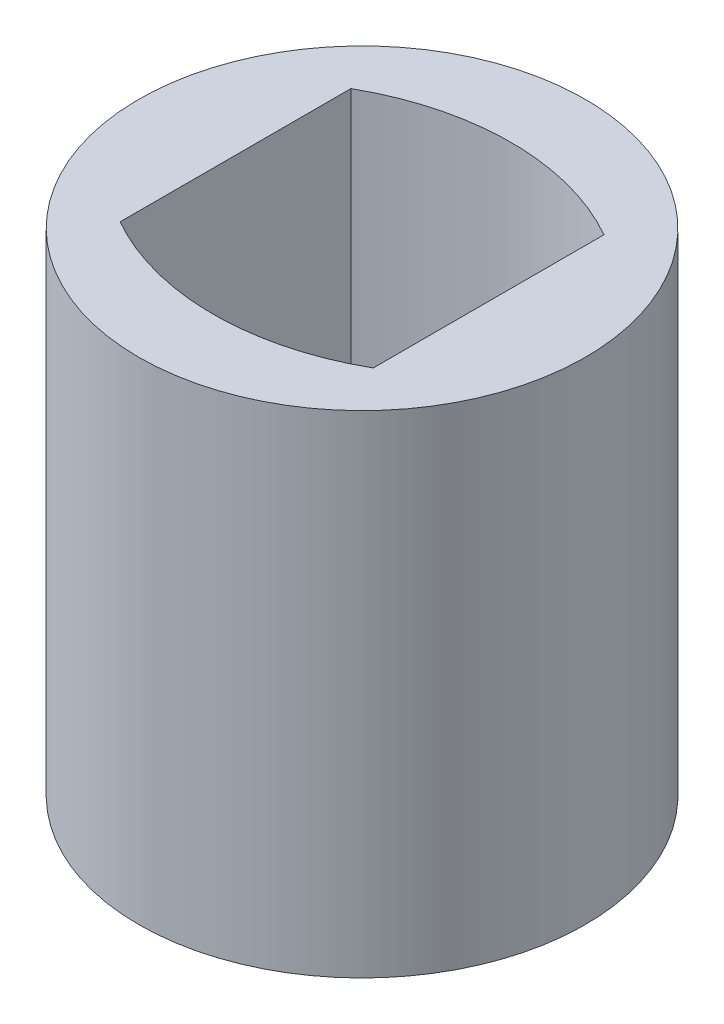
SolidWorks part; units mm, degrees
ref_plane "Front Plane" through (0, 0, 0) normal (0, 0, 1) x (1, 0, 0)
ref_plane "Top Plane" through (0, 0, 0) normal (0, 1, 0) x (1, 0, 0)
ref_plane "Right Plane" through (0, 0, 0) normal (1, 0, 0) x (0, 0, -1)
sketch "Sketch2" plane through (0, 0, 0) normal (0, 1, 0) x (1, 0, 0)
  circle A0 centre (0, 0) radius 3.81
  dimension "D1" = 7.62
extrude "Boss-Extrude1" add sketch "Sketch2" along normal mid plane 2.54
sketch "Sketch3" plane through (0, -1.27, 0) normal (0, -1, 0) x (1, 0, 0)
  line L0 (-0.889, 1.0922) -> (-0.889, -1.0922)
  line L1 (0.889, 1.0922) -> (0.889, -1.0922)
  line L2 (-1.8541, 0) -> (3.3125, 0) construction
  line L3 (0, 1.6302) -> (0, -1.2135) construction
  arc A0 (-0.889, 1.0922) -> (0.889, 1.0922) centre (0, -0.0519) cw
  arc A1 (-0.889, -1.0922) -> (0.889, -1.0922) centre (0, 0.0519) ccw
  point P7 (0.889, 0)
  point P8 (-0.889, 0)
  point P13 (0, 1.397)
  point P14 (0, -1.397)
  dimension "D1" = 2.1844
  dimension "D2" = 1.778
  dimension "D3" = 2.794
extrude "Boss-Extrude2" add sketch "Sketch3" along normal blind 1.27
sketch "Sketch4" plane through (0, 1.27, 0) normal (0, 1, 0) x (1, 0, 0)
  line L0 (-2.159, 1.9685) -> (-2.159, -1.9685)
  line L1 (2.159, 1.9685) -> (2.159, -1.9685)
  line L2 (-1.7553, 0) -> (1.9988, 0) construction
  line L3 (0, 1.4661) -> (0, -1.5676) construction
  arc A0 (-2.159, -1.9685) -> (2.159, -1.9685) centre (0, 1.8239) ccw
  arc A1 (-2.159, 1.9685) -> (2.159, 1.9685) centre (0, -1.8239) cw
  point P11 (-8.4414, 2.6938)
  point P12 (-2.159, 1.2936)
  point P13 (2.159, 1.4661)
  point P14 (2.159, 0)
  point P15 (-2.159, 0)
  point P16 (0, 2.54)
  point P17 (0, -2.54)
  circle M5 centre (0, 0) radius 3.81
  dimension "D1" = 4.318
  dimension "D2" = 5.08
  dimension "D3" = 3.937
extrude "Boss-Extrude3" add sketch "Sketch4" along normal blind 5.842 contours L0 A1 L1 A0 M5
